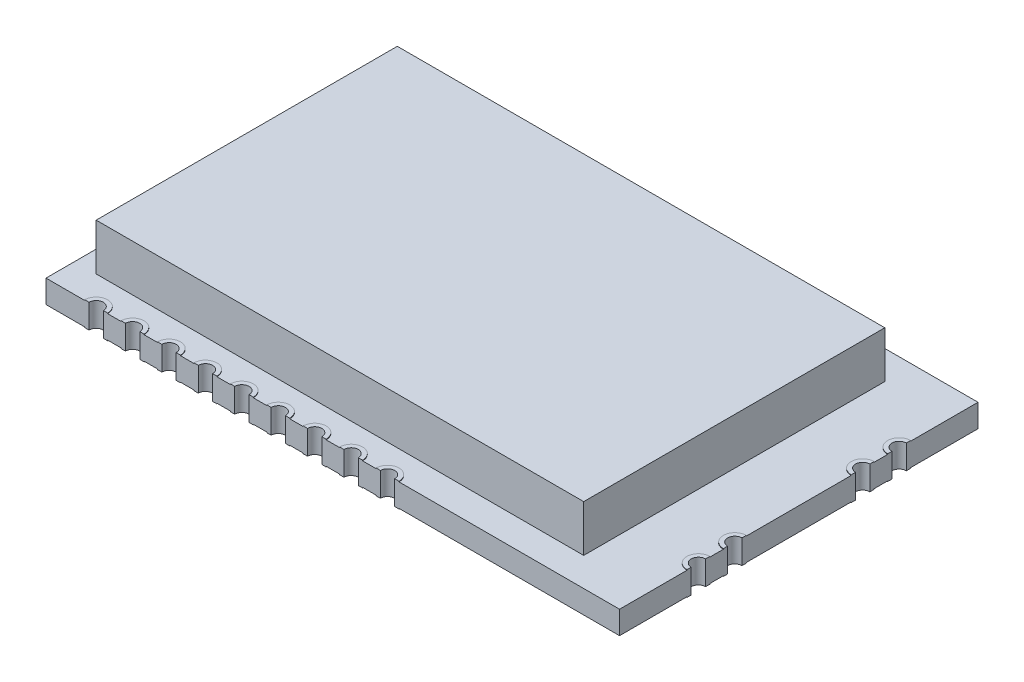
SolidWorks part; units mm, degrees
ref_plane "Front Plane" through (0, 0, 0) normal (0, 0, 1) x (1, 0, 0)
ref_plane "Top Plane" through (0, 0, 0) normal (0, 1, 0) x (1, 0, 0)
ref_plane "Right Plane" through (0, 0, 0) normal (1, 0, 0) x (0, 0, -1)
sketch "Sketch1" plane through (0, 0, 0) normal (0, 1, 0) x (1, 0, 0)
  line L1 (20, 12.5) -> (-20, 12.5)
  line L2 (20, 12.5) -> (20, -12.5)
  line L3 (20, -12.5) -> (-20, -12.5)
  line L4 (-20, 12.5) -> (-20, -12.5)
  circle A0 centre (-16.5, 12.5) radius 0.5
  circle A1 centre (-13.96, 12.5) radius 0.5
  circle A2 centre (-11.42, 12.5) radius 0.5
  circle A3 centre (-8.88, 12.5) radius 0.5
  circle A4 centre (-6.34, 12.5) radius 0.5
  circle A5 centre (-3.8, 12.5) radius 0.5
  circle A7 centre (-1.26, 12.5) radius 0.5
  circle A8 centre (1.28, 12.5) radius 0.5
  circle A9 centre (3.82, 12.5) radius 0.5
  circle A10 centre (-16.5, -12.5) radius 0.5
  circle A11 centre (-13.96, -12.5) radius 0.5
  circle A12 centre (-11.42, -12.5) radius 0.5
  circle A13 centre (-8.88, -12.5) radius 0.5
  circle A14 centre (-6.34, -12.5) radius 0.5
  circle A15 centre (-3.8, -12.5) radius 0.5
  circle A16 centre (-1.26, -12.5) radius 0.5
  circle A17 centre (1.28, -12.5) radius 0.5
  circle A18 centre (3.82, -12.5) radius 0.5
  circle A19 centre (20, -7) radius 0.5
  circle A20 centre (20, -4.46) radius 0.5
  circle A21 centre (20, 4.46) radius 0.5
  circle A22 centre (20, 7) radius 0.5
  dimension "D5" = 1
  dimension "D1" = 40
  dimension "D2" = 25
  dimension "D3" = 20
  dimension "D4" = 12.5
  dimension "D6" = 3.5
  dimension "D7" = 2.54
  dimension "D8" = 2.54
  dimension "D9" = 2.54
  dimension "D10" = 2.54
  dimension "D11" = 2.54
  dimension "D12" = 2.54
  dimension "D13" = 2.54
  dimension "D14" = 2.54
  dimension "D15" = 5.5
  dimension "D16" = 2.54
  dimension "D17" = 5.5
  dimension "D18" = 2.54
extrude "Boss-Extrude1" add sketch "Sketch1" along normal blind 1.6 contours A22 L2 L1 A9 A8 A7 A5 A4 A3 A2 A1 A0 L4 L3 A10 A11 A12 A13 A14 A15 A16 A17 A18 A19 A20 A21
sketch "Sketch2" plane through (0, 1.6, 0) normal (0, 1, 0) x (1, 0, 0)
  line L0 (-17, 12.5) -> (-17.3, 12.5)
  line L1 (-16, 12.5) -> (-15.7, 12.5)
  line L2 (20, -7.5) -> (20, -12.5) construction
  line L3 (-14.76, 12.5) -> (-14.46, 12.5)
  line L4 (-13.46, 12.5) -> (-13.16, 12.5)
  line L5 (4.32, 12.5) -> (4.62, 12.5)
  line L6 (3.32, 12.5) -> (3.02, 12.5)
  line L7 (2.08, 12.5) -> (1.78, 12.5)
  line L8 (-0.76, 12.5) -> (-0.46, 12.5)
  line L9 (-2.06, 12.5) -> (-1.76, 12.5)
  line L10 (-4.6, 12.5) -> (-4.3, 12.5)
  line L11 (-3, 12.5) -> (-3.3, 12.5)
  line L12 (-7.14, 12.5) -> (-6.84, 12.5)
  line L13 (-5.84, 12.5) -> (-5.54, 12.5)
  line L14 (-8.38, 12.5) -> (-8.08, 12.5)
  line L15 (-9.68, 12.5) -> (-9.38, 12.5)
  line L16 (-12.22, 12.5) -> (-11.92, 12.5)
  line L17 (-10.92, 12.5) -> (-10.62, 12.5)
  line L18 (0.48, 12.5) -> (0.78, 12.5)
  line L19 (-17.3, -12.5) -> (-17, -12.5)
  line L20 (-16, -12.5) -> (-15.7, -12.5)
  line L21 (4.32, -12.5) -> (4.62, -12.5)
  line L22 (3.32, -12.5) -> (3.02, -12.5)
  line L23 (1.78, -12.5) -> (2.08, -12.5)
  line L24 (0.78, -12.5) -> (0.48, -12.5)
  line L25 (-2.06, -12.5) -> (-1.76, -12.5)
  line L26 (-0.76, -12.5) -> (-0.46, -12.5)
  line L27 (-4.6, -12.5) -> (-4.3, -12.5)
  line L28 (-3.3, -12.5) -> (-3, -12.5)
  line L29 (-7.14, -12.5) -> (-6.84, -12.5)
  line L30 (-5.84, -12.5) -> (-5.54, -12.5)
  line L31 (-9.68, -12.5) -> (-9.38, -12.5)
  line L32 (-8.38, -12.5) -> (-8.08, -12.5)
  line L33 (-12.22, -12.5) -> (-11.92, -12.5)
  line L34 (-10.92, -12.5) -> (-10.62, -12.5)
  line L35 (-14.76, -12.5) -> (-14.46, -12.5)
  line L36 (-13.46, -12.5) -> (-13.16, -12.5)
  line L37 (20, -6.2) -> (20, -6.5)
  line L38 (20, 3.96) -> (20, -3.96) construction
  line L39 (20, 7.8) -> (20, 7.5)
  line L40 (20, 6.5) -> (20, 6.2)
  line L41 (20, 5.26) -> (20, 4.96)
  line L42 (20, 3.96) -> (20, 3.66)
  line L43 (20, -3.66) -> (20, -3.96)
  line L44 (20, -4.96) -> (20, -5.26)
  line L46 (20, -7.5) -> (20, -7.8)
  arc A1 (-17.3, 12.5) -> (-15.7, 12.5) centre (-16.5, 12.5) ccw
  arc A3 (-14.76, 12.5) -> (-13.16, 12.5) centre (-13.96, 12.5) ccw
  arc A4 (-12.22, 12.5) -> (-10.62, 12.5) centre (-11.42, 12.5) ccw
  arc A5 (-9.68, 12.5) -> (-8.08, 12.5) centre (-8.88, 12.5) ccw
  arc A6 (-7.14, 12.5) -> (-5.54, 12.5) centre (-6.34, 12.5) ccw
  arc A7 (-2.06, 12.5) -> (-0.46, 12.5) centre (-1.26, 12.5) ccw
  arc A8 (0.48, 12.5) -> (2.08, 12.5) centre (1.28, 12.5) ccw
  arc A9 (3.02, 12.5) -> (4.62, 12.5) centre (3.82, 12.5) ccw
  arc A11 (-4.6, 12.5) -> (-3, 12.5) centre (-3.8, 12.5) ccw
  arc A12 (-13.16, -12.5) -> (-14.76, -12.5) centre (-13.96, -12.5) ccw
  arc A13 (-15.7, -12.5) -> (-17.3, -12.5) centre (-16.5, -12.5) ccw
  arc A14 (-10.62, -12.5) -> (-12.22, -12.5) centre (-11.42, -12.5) ccw
  arc A15 (-8.08, -12.5) -> (-9.68, -12.5) centre (-8.88, -12.5) ccw
  arc A16 (-5.54, -12.5) -> (-7.14, -12.5) centre (-6.34, -12.5) ccw
  arc A17 (-3, -12.5) -> (-4.6, -12.5) centre (-3.8, -12.5) ccw
  arc A18 (-0.46, -12.5) -> (-2.06, -12.5) centre (-1.26, -12.5) ccw
  arc A19 (2.08, -12.5) -> (0.48, -12.5) centre (1.28, -12.5) ccw
  arc A20 (4.62, -12.5) -> (3.02, -12.5) centre (3.82, -12.5) ccw
  arc A21 (20, -3.66) -> (20, -5.26) centre (20, -4.46) ccw
  arc A22 (20, -6.2) -> (20, -7.8) centre (20, -7) ccw
  arc A23 (20, 5.26) -> (20, 3.66) centre (20, 4.46) ccw
  arc A24 (20, 7.8) -> (20, 6.2) centre (20, 7) ccw
  arc A25 (-17, 12.5) -> (-16, 12.5) centre (-16.5, 12.5) ccw
  arc A26 (-17, 12.5) -> (-16, 12.5) centre (-16.5, 12.5) ccw construction
  arc A27 (-14.46, 12.5) -> (-13.46, 12.5) centre (-13.96, 12.5) ccw
  arc A28 (-11.92, 12.5) -> (-10.92, 12.5) centre (-11.42, 12.5) ccw
  arc A29 (-9.38, 12.5) -> (-8.38, 12.5) centre (-8.88, 12.5) ccw
  arc A30 (-6.84, 12.5) -> (-5.84, 12.5) centre (-6.34, 12.5) ccw
  arc A31 (-4.3, 12.5) -> (-3.3, 12.5) centre (-3.8, 12.5) ccw
  arc A32 (-1.76, 12.5) -> (-0.76, 12.5) centre (-1.26, 12.5) ccw
  arc A33 (0.78, 12.5) -> (1.78, 12.5) centre (1.28, 12.5) ccw
  arc A34 (3.32, 12.5) -> (4.32, 12.5) centre (3.82, 12.5) ccw
  arc A35 (-16, -12.5) -> (-17, -12.5) centre (-16.5, -12.5) ccw
  arc A36 (-16, -12.5) -> (-17, -12.5) centre (-16.5, -12.5) ccw construction
  arc A37 (-13.46, -12.5) -> (-14.46, -12.5) centre (-13.96, -12.5) ccw
  arc A38 (-10.92, -12.5) -> (-11.92, -12.5) centre (-11.42, -12.5) ccw
  arc A39 (-8.38, -12.5) -> (-9.38, -12.5) centre (-8.88, -12.5) ccw
  arc A40 (-5.84, -12.5) -> (-6.84, -12.5) centre (-6.34, -12.5) ccw
  arc A41 (-3.3, -12.5) -> (-4.3, -12.5) centre (-3.8, -12.5) ccw
  arc A42 (-0.76, -12.5) -> (-1.76, -12.5) centre (-1.26, -12.5) ccw
  arc A43 (1.78, -12.5) -> (0.78, -12.5) centre (1.28, -12.5) ccw
  arc A44 (4.32, -12.5) -> (3.32, -12.5) centre (3.82, -12.5) ccw
  arc A47 (20, -4.96) -> (20, -3.96) centre (20, -4.46) cw
  arc A48 (20, 3.96) -> (20, 4.96) centre (20, 4.46) cw
  arc A49 (20, 6.5) -> (20, 7.5) centre (20, 7) cw
  arc A51 (20, -7.5) -> (20, -6.5) centre (20, -7) cw
extrude "Boss-Extrude2" add sketch "Sketch2" along normal blind 0.04
sketch "Sketch9" plane through (0, 0, 0) normal (0, -1, 0) x (-1, 0, 0)
  line L0 (17, 12.5) -> (17.299, 12.5)
  line L1 (17, 12.5) -> (20, 12.5) construction
  line L2 (17.299, 12.5) -> (17.299, 10.505)
  line L3 (17.299, 10.505) -> (15.6944, 10.505)
  line L4 (15.6944, 10.505) -> (15.6944, 12.5)
  line L5 (14.46, 12.5) -> (16, 12.5) construction
  line L6 (15.6944, 12.5) -> (16, 12.5)
  line L7 (14.46, 12.5) -> (14.76, 12.5)
  line L8 (14.76, 12.5) -> (14.76, 10.505)
  line L9 (14.76, 10.505) -> (13.16, 10.505)
  line L10 (13.16, 10.505) -> (13.16, 12.5)
  line L11 (13.16, 12.5) -> (13.46, 12.5)
  line L12 (11.92, 12.5) -> (12.22, 12.5)
  line L13 (12.22, 12.5) -> (12.22, 10.505)
  line L14 (12.22, 10.505) -> (10.62, 10.505)
  line L15 (10.62, 10.505) -> (10.62, 12.5)
  line L16 (10.62, 12.5) -> (10.92, 12.5)
  line L17 (11.92, 12.5) -> (13.46, 12.5) construction
  line L18 (9.38, 12.5) -> (9.68, 12.5)
  line L19 (9.68, 12.5) -> (9.68, 10.505)
  line L20 (9.68, 10.505) -> (8.08, 10.505)
  line L21 (8.08, 10.505) -> (8.08, 12.5)
  line L22 (8.08, 12.5) -> (8.38, 12.5)
  line L23 (9.38, 12.5) -> (10.92, 12.5) construction
  line L24 (6.84, 12.5) -> (7.14, 12.5)
  line L25 (7.14, 12.5) -> (7.14, 10.505)
  line L26 (7.14, 10.505) -> (5.54, 10.505)
  line L27 (5.54, 10.505) -> (5.54, 12.5)
  line L28 (5.54, 12.5) -> (5.84, 12.5)
  line L29 (4.3, 12.5) -> (4.6, 12.5)
  line L30 (4.6, 12.5) -> (4.6, 10.505)
  line L31 (4.6, 10.505) -> (3, 10.505)
  line L32 (3, 10.505) -> (3, 12.5)
  line L33 (3, 12.5) -> (3.3, 12.5)
  line L34 (1.76, 12.5) -> (2.06, 12.5)
  line L35 (2.06, 12.5) -> (2.06, 10.505)
  line L36 (2.06, 10.505) -> (0.46, 10.505)
  line L37 (0.46, 10.505) -> (0.46, 12.5)
  line L38 (0.46, 12.5) -> (0.76, 12.5)
  line L39 (-0.78, 12.5) -> (-0.48, 12.5)
  line L40 (-0.48, 12.5) -> (-0.48, 10.505)
  line L41 (-0.48, 10.505) -> (-2.08, 10.505)
  line L42 (-2.08, 10.505) -> (-2.08, 12.5)
  line L43 (-2.08, 12.5) -> (-1.78, 12.5)
  line L44 (-3.32, 12.5) -> (-3.02, 12.5)
  line L45 (-3.02, 12.5) -> (-3.02, 10.505)
  line L46 (-3.02, 10.505) -> (-4.62, 10.505)
  line L47 (-4.62, 10.505) -> (-4.62, 12.5)
  line L48 (-4.62, 12.5) -> (-4.32, 12.5)
  line L49 (17, -12.5) -> (17.3, -12.5)
  line L50 (17.3, -12.5) -> (17.3, -10.5)
  line L51 (17.3, -10.5) -> (15.7, -10.5)
  line L52 (15.7, -10.5) -> (15.7, -12.5)
  line L53 (15.7, -12.5) -> (16, -12.5)
  line L54 (14.46, -12.5) -> (14.76, -12.5)
  line L55 (14.76, -12.5) -> (14.76, -10.5)
  line L56 (14.76, -10.5) -> (13.16, -10.5)
  line L57 (13.16, -10.5) -> (13.16, -12.5)
  line L58 (13.16, -12.5) -> (13.46, -12.5)
  line L59 (11.92, -12.5) -> (12.22, -12.5)
  line L60 (12.22, -12.5) -> (12.22, -10.5)
  line L61 (12.22, -10.5) -> (10.62, -10.5)
  line L62 (10.62, -10.5) -> (10.62, -12.5)
  line L63 (10.62, -12.5) -> (10.92, -12.5)
  line L64 (9.38, -12.5) -> (10.92, -12.5) construction
  line L65 (9.38, -12.5) -> (9.68, -12.5)
  line L66 (9.68, -12.5) -> (9.68, -10.5)
  line L67 (9.68, -10.5) -> (8.0819, -10.5)
  line L68 (8.0819, -10.5) -> (8.08, -12.5)
  line L69 (8.08, -12.5) -> (8.38, -12.5)
  line L70 (6.84, -12.5) -> (7.14, -12.5)
  line L71 (7.14, -12.5) -> (7.14, -10.5)
  line L72 (7.14, -10.5) -> (5.54, -10.5)
  line L73 (5.54, -10.5) -> (5.54, -12.5)
  line L74 (5.54, -12.5) -> (5.84, -12.5)
  line L75 (6.84, -12.5) -> (8.38, -12.5) construction
  line L76 (4.3, -12.5) -> (4.6, -12.5)
  line L77 (4.6, -12.5) -> (4.6, -10.5)
  line L78 (4.6, -10.5) -> (3.0082, -10.5)
  line L79 (3.0082, -10.5) -> (3.0082, -12.5)
  line L80 (3.0082, -12.5) -> (3.3, -12.5)
  line L81 (1.76, -12.5) -> (3.3, -12.5) construction
  line L82 (1.76, -12.5) -> (2.06, -12.5)
  line L83 (2.06, -12.5) -> (2.06, -10.5)
  line L84 (2.06, -10.5) -> (0.46, -10.5)
  line L85 (0.46, -10.5) -> (0.46, -12.5)
  line L86 (0.46, -12.5) -> (0.76, -12.5)
  line L87 (-0.78, -12.5) -> (0.76, -12.5) construction
  line L88 (-0.78, -12.5) -> (-0.48, -12.5)
  line L89 (-0.48, -12.5) -> (-0.48, -10.5)
  line L90 (-0.48, -10.5) -> (-2.08, -10.5)
  line L91 (-2.08, -10.5) -> (-2.08, -12.5)
  line L92 (-2.08, -12.5) -> (-1.78, -12.5)
  line L93 (-3.32, -12.5) -> (-1.78, -12.5) construction
  line L94 (-3.32, -12.5) -> (-3.02, -12.5)
  line L95 (-3.02, -12.5) -> (-3.02, -10.5)
  line L96 (-3.02, -10.5) -> (-4.62, -10.5)
  line L97 (-4.62, -10.5) -> (-4.62, -12.5)
  line L98 (-4.62, -12.5) -> (-4.32, -12.5)
  line L99 (-20, -12.5) -> (-4.32, -12.5) construction
  line L100 (-20, 7.5) -> (-20, 7.8)
  line L101 (-20, 12.5) -> (-20, 7.5) construction
  line L102 (-20, 7.8) -> (-18, 7.8)
  line L103 (-18, 7.8) -> (-18, 6.2)
  line L104 (-18, 6.2) -> (-20, 6.2)
  line L105 (-20, 6.5) -> (-20, 4.96) construction
  line L106 (-20, 6.2) -> (-20, 6.5)
  line L107 (-20, 4.96) -> (-20, 5.26)
  line L108 (-20, 5.26) -> (-18, 5.26)
  line L109 (-18, 5.26) -> (-18, 3.66)
  line L110 (-18, 3.66) -> (-20, 3.66)
  line L111 (-20, 3.66) -> (-20, 3.96)
  line L112 (-20, 3.96) -> (-20, -3.96) construction
  line L113 (-20, -3.96) -> (-20, -3.66)
  line L114 (-20, -3.66) -> (-18, -3.66)
  line L115 (-18, -3.66) -> (-18, -5.26)
  line L116 (-18, -5.26) -> (-20, -5.26)
  line L117 (-20, -5.26) -> (-20, -4.96)
  line L118 (-20, -6.5) -> (-20, -6.2)
  line L119 (-20, -6.2) -> (-18, -6.2)
  line L120 (-18, -6.2) -> (-18, -7.8)
  line L121 (-18, -7.8) -> (-20, -7.8)
  line L122 (-20, -7.8) -> (-20, -7.5)
  arc A0 (13.46, 12.5) -> (14.46, 12.5) centre (13.96, 12.5) ccw
  arc A1 (16, 12.5) -> (17, 12.5) centre (16.5, 12.5) ccw
  arc A2 (16, 12.5) -> (17, 12.5) centre (16.5, 12.5) ccw construction
  arc A3 (10.92, 12.5) -> (11.92, 12.5) centre (11.42, 12.5) ccw
  arc A4 (8.38, 12.5) -> (9.38, 12.5) centre (8.88, 12.5) ccw
  arc A5 (8.38, 12.5) -> (9.38, 12.5) centre (8.88, 12.5) ccw construction
  arc A6 (5.84, 12.5) -> (6.84, 12.5) centre (6.34, 12.5) ccw
  arc A7 (3.3, 12.5) -> (4.3, 12.5) centre (3.8, 12.5) ccw
  arc A8 (0.76, 12.5) -> (1.76, 12.5) centre (1.26, 12.5) ccw
  arc A9 (-1.78, 12.5) -> (-0.78, 12.5) centre (-1.28, 12.5) ccw
  arc A10 (-4.32, 12.5) -> (-3.32, 12.5) centre (-3.82, 12.5) ccw
  arc A11 (17, -12.5) -> (16, -12.5) centre (16.5, -12.5) ccw
  arc A12 (17, -12.5) -> (16, -12.5) centre (16.5, -12.5) ccw construction
  arc A13 (14.46, -12.5) -> (13.46, -12.5) centre (13.96, -12.5) ccw
  arc A14 (11.92, -12.5) -> (10.92, -12.5) centre (11.42, -12.5) ccw
  arc A15 (9.38, -12.5) -> (8.38, -12.5) centre (8.88, -12.5) ccw
  arc A16 (6.84, -12.5) -> (5.84, -12.5) centre (6.34, -12.5) ccw
  arc A17 (4.3, -12.5) -> (3.3, -12.5) centre (3.8, -12.5) ccw
  arc A18 (1.76, -12.5) -> (0.76, -12.5) centre (1.26, -12.5) ccw
  arc A19 (-0.78, -12.5) -> (-1.78, -12.5) centre (-1.28, -12.5) ccw
  arc A20 (-3.32, -12.5) -> (-4.32, -12.5) centre (-3.82, -12.5) ccw
  arc A21 (-20, 7.5) -> (-20, 6.5) centre (-20, 7) cw
  arc A22 (-20, 6.5) -> (-20, 7.5) centre (-20, 7) ccw construction
  arc A23 (-20, 4.96) -> (-20, 3.96) centre (-20, 4.46) cw
  arc A24 (-20, -3.96) -> (-20, -4.96) centre (-20, -4.46) cw
  arc A25 (-20, -6.5) -> (-20, -7.5) centre (-20, -7) cw
  dimension "D1" = 0.3
  dimension "D2" = 0.3
  dimension "D3" = 2
  dimension "D4" = 1.6
  dimension "D5" = 0.3
  dimension "D6" = 0.3
  dimension "D7" = 2
  dimension "D8" = 1.6
  dimension "D9" = 2
extrude "Boss-Extrude3" add sketch "Sketch9" along normal blind 0.04
sketch "Sketch11" plane through (0, 1.6, 0) normal (0, 1, 0) x (1, 0, 0)
  line L0 (-17.3, -12.5) -> (-20, -12.5) construction
  line L1 (-18.5, 10.5) -> (15.5, 10.5)
  line L2 (-18.5, 10.5) -> (-18.5, -10.5)
  line L3 (-18.5, -10.5) -> (15.5, -10.5)
  line L4 (15.5, 10.5) -> (15.5, -10.5)
  line L5 (-20, 12.5) -> (-20, -12.5) construction
  dimension "D1" = 21
  dimension "D2" = 2
  dimension "D3" = 1.5
  dimension "D4" = 34
extrude "Boss-Extrude5" add sketch "Sketch11" along normal blind 3.25
